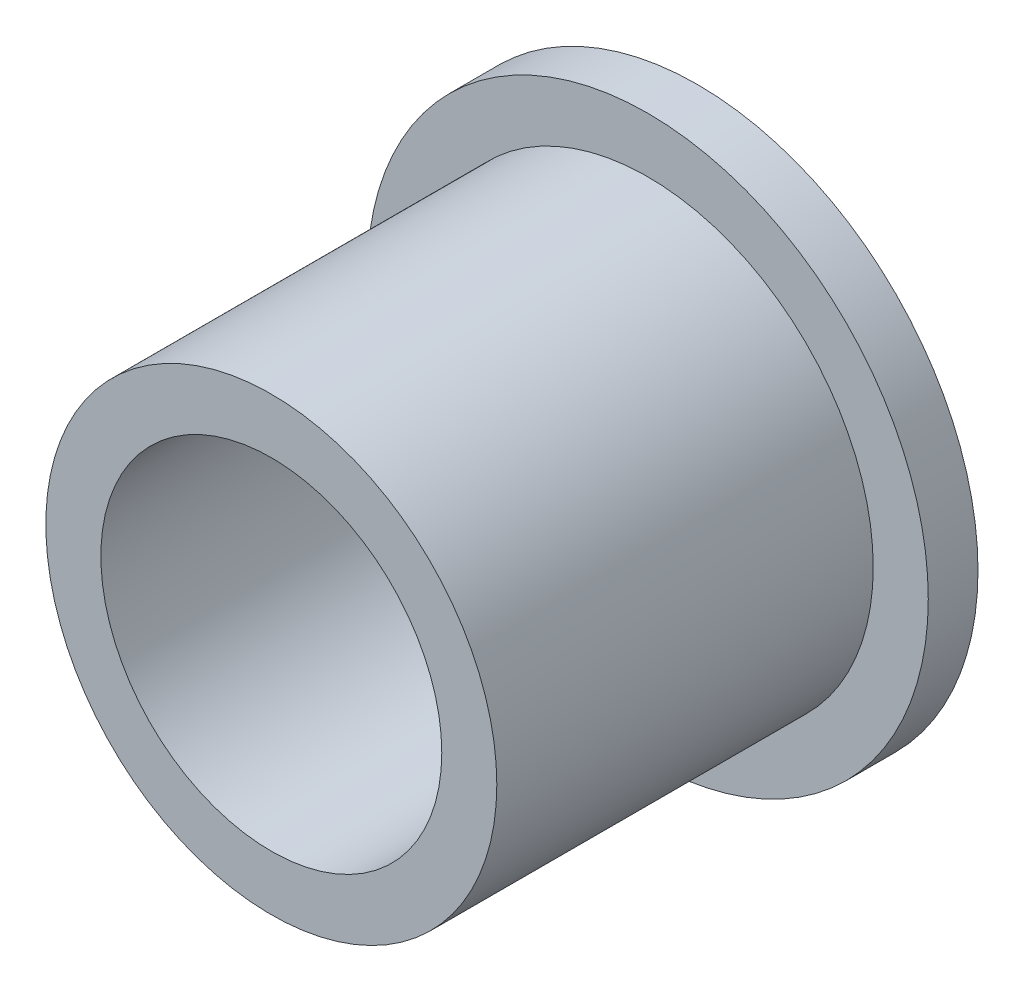
SolidWorks part; units mm, degrees
ref_plane "Front Plane" through (0, 0, 0) normal (0, 0, 1) x (1, 0, 0)
ref_plane "Top Plane" through (0, 0, 0) normal (0, 1, 0) x (1, 0, 0)
ref_plane "Right Plane" through (0, 0, 0) normal (1, 0, 0) x (0, 0, -1)
sketch "Sketch1" plane through (0, 0, 0) normal (0, 0, 1) x (1, 0, 0)
  circle A0 centre (0, 0) radius 4.8
  circle A1 centre (0, 0) radius 7.9
  dimension "D1" = 9.6
  dimension "D2" = 15.8
extrude "Boss-Extrude1" add sketch "Sketch1" along normal blind 12
sketch "Sketch2" plane through (0, 0, 12) normal (0, 0, 1) x (1, 0, 0)
  circle A0 centre (0, 0) radius 10.1452
  circle A1 centre (0, 0) radius 6.35
  dimension "D1" = 12.7
extrude "Cut-Extrude1" cut sketch "Sketch2" against normal offset from surface (10.6 mm away) 1.4 up to face at (7.9, 0, 0)
